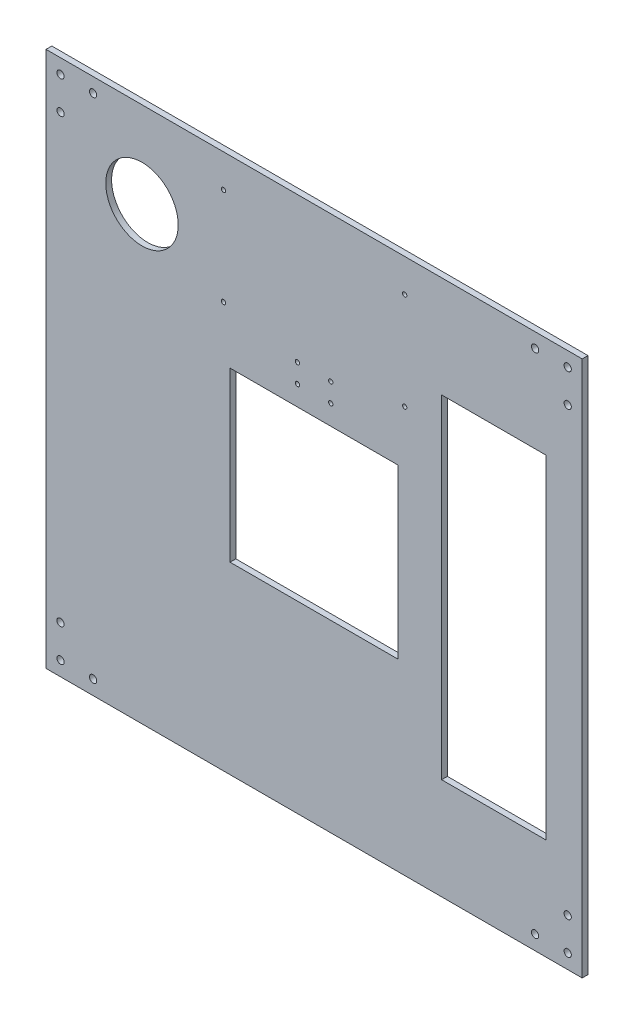
SolidWorks part; units mm, degrees
ref_plane "前视基准面" through (0, 0, 0) normal (0, 0, 1) x (1, 0, 0)
ref_plane "上视基准面" through (0, 0, 0) normal (0, 1, 0) x (1, 0, 0)
ref_plane "右视基准面" through (0, 0, 0) normal (1, 0, 0) x (0, 0, -1)
sketch "草图1" plane through (0, 0, 0) normal (0, 0, 1) x (1, 0, 0)
  line L1 (185, -185) -> (-185, -185)
  line L2 (185, -185) -> (185, 185)
  line L3 (185, 185) -> (-185, 185)
  line L4 (-185, -185) -> (-185, 185)
  line L5 (185, -185) -> (-185, 185) construction
  line L6 (185, 185) -> (-185, -185) construction
  point P0 (0, 0)
  dimension "D1" = 370
  dimension "D2" = 370
extrude "凸台-拉伸1" add sketch "草图1" along normal blind 4
sketch "草图2" plane through (0, 0, 4) normal (0, 0, 1) x (1, 0, 0)
  line L0 (-165, -175) -> (-152.5, -175) construction
  line L1 (-185, -185) -> (-165, -185) construction
  line L2 (-185, -185) -> (-185, -165) construction
  line L3 (-185, -165) -> (-165, -165) construction
  line L4 (-165, -185) -> (-165, -165) construction
  line L5 (-175, -165) -> (-175, -152.5) construction
  circle A0 centre (-175, -175) radius 2.5
  circle A1 centre (-152.5, -175) radius 2.5
  circle A2 centre (-175, -152.5) radius 2.5
  circle A3 centre (-152.5, 175) radius 2.5
  circle A4 centre (-175, 152.5) radius 2.5
  circle A5 centre (-175, 175) radius 2.5
  circle A6 centre (175, 152.5) radius 2.5
  circle A7 centre (152.5, 175) radius 2.5
  circle A8 centre (175, 175) radius 2.5
  circle A9 centre (152.5, -175) radius 2.5
  circle A10 centre (175, -152.5) radius 2.5
  circle A11 centre (175, -175) radius 2.5
  point P34 (0, 0)
  dimension "D3" = 10
  dimension "D4" = 10
  dimension "D5" = 5
  dimension "D6" = 12.5
  dimension "D7" = 5
  dimension "D9" = 5
  dimension "D1" = 20
  dimension "D2" = 20
  dimension "D8" = 12.5
  dimension "D10" = 4
extrude "切除-拉伸1" cut sketch "草图2" against normal through all
sketch "草图6" plane through (0, 0, 0) normal (0, 0, -1) x (-1, 0, 0)
  line L1 (62.5, 95.2498) -> (-62.5, 95.2498) construction
  line L2 (62.5, 95.2498) -> (62.5, 162.2498) construction
  line L3 (62.5, 162.2498) -> (-62.5, 162.2498) construction
  line L4 (-62.5, 95.2498) -> (-62.5, 162.2498) construction
  line L5 (62.5, 95.2498) -> (-62.5, 162.2498) construction
  line L6 (62.5, 162.2498) -> (-62.5, 95.2498) construction
  circle A0 centre (-62.5, 162.2498) radius 1.5
  circle A1 centre (-62.5, 95.2498) radius 1.5
  circle A2 centre (62.5, 95.2498) radius 1.5
  circle A3 centre (62.5, 162.2498) radius 1.5
  point P0 (0, 128.7498)
  dimension "D3" = 3
  dimension "D4" = 3
  dimension "D5" = 3
  dimension "D6" = 3
  dimension "D1" = 67
  dimension "D2" = 125
extrude "切除-拉伸7" cut sketch "草图6" against normal through all
sketch "草图7" plane through (0, 0, 0) normal (0, 0, -1) x (-1, 0, 0)
  circle A0 centre (118.7699, 125.6318) radius 25
  dimension "D1" = 50
extrude "切除-拉伸8" cut sketch "草图7" against normal through all
sketch "草图8" plane through (0, 0, 0) normal (0, 0, -1) x (-1, 0, 0)
  line L1 (58, -58) -> (-58, -58)
  line L2 (58, -58) -> (58, 58)
  line L3 (58, 58) -> (-58, 58)
  line L4 (-58, -58) -> (-58, 58)
  line L5 (58, -58) -> (-58, 58) construction
  line L6 (58, 58) -> (-58, -58) construction
  point P0 (0, 0)
  dimension "D1" = 116
  dimension "D2" = 116
extrude "切除-拉伸9" cut sketch "草图8" against normal blind 10
sketch "草图11" plane through (0, 0, 0) normal (0, 0, -1) x (-1, 0, 0)
  line L0 (0, 0) -> (-185, 0) construction
  line L1 (-185, -185) -> (-185, 185) construction
  line L3 (-88, -115) -> (-160, -115)
  line L4 (-88, -115) -> (-88, 115)
  line L5 (-88, 115) -> (-160, 115)
  line L6 (-160, -115) -> (-160, 115)
  line L7 (-88, -115) -> (-160, 115) construction
  line L8 (-88, 115) -> (-160, -115) construction
  line L9 (-58, 58) -> (-58, -58) construction
  point P5 (-124, 0)
  dimension "D1" = 30
  dimension "D2" = 230
  dimension "D3" = 25
extrude "切除-拉伸11" cut sketch "草图11" against normal blind 5
sketch "草图12" plane through (0, 0, 0) normal (0, 0, -1) x (-1, 0, 0)
  circle A0 centre (-11.5, 71.7321) radius 1.5
  circle A1 centre (11.5, 71.7321) radius 1.5
  circle A2 centre (-11.5, 84.7321) radius 1.5
  circle A3 centre (11.5, 84.7321) radius 1.5
extrude "切除-拉伸12" cut sketch "草图12" against normal through all
